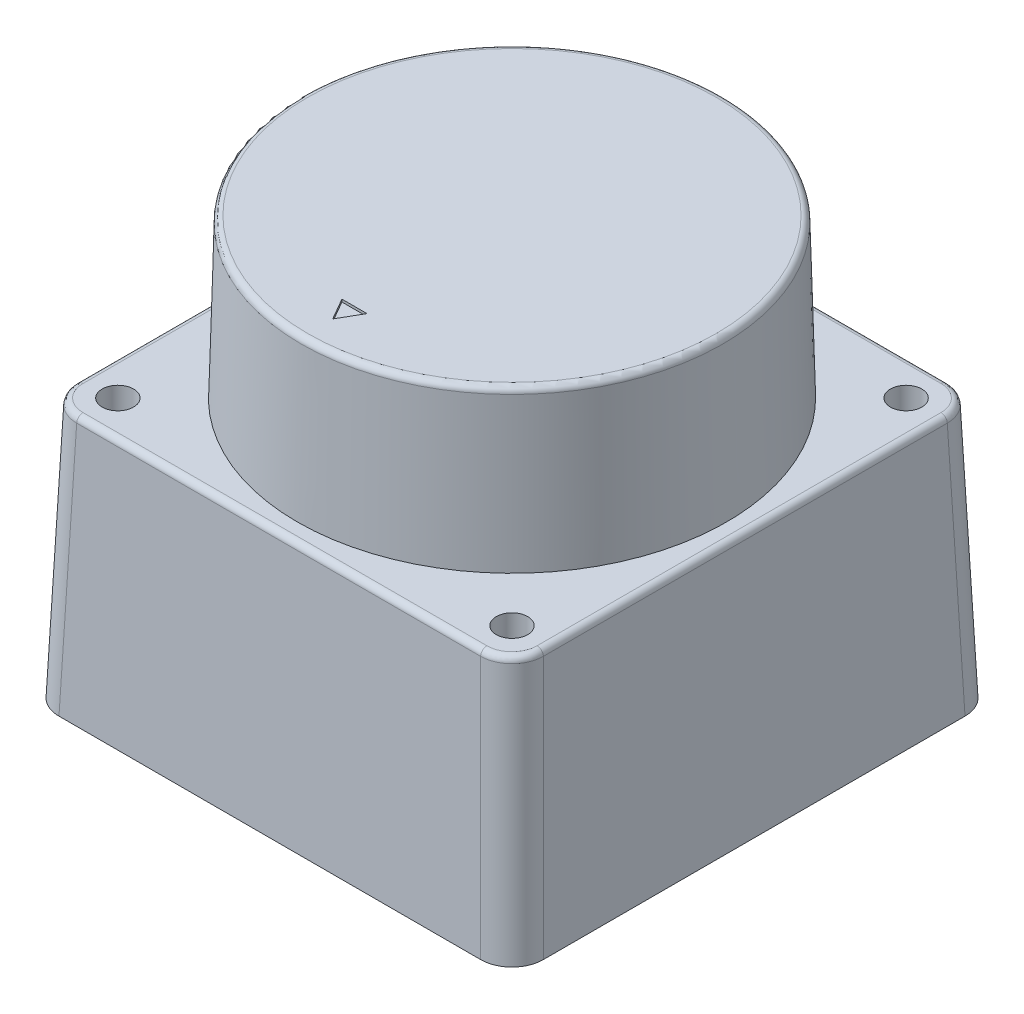
SolidWorks part; units mm, degrees
ref_plane "Płaszczyzna przednia" through (0, 0, 0) normal (0, 0, 1) x (1, 0, 0)
ref_plane "Płaszczyzna górna" through (0, 0, 0) normal (0, 1, 0) x (1, 0, 0)
ref_plane "Płaszczyzna prawa" through (0, 0, 0) normal (1, 0, 0) x (0, 0, -1)
sketch "Szkic1" plane through (0, 0, 0) normal (0, 1, 0) x (1, 0, 0)
  line L1 (-19.295, 19.295) -> (19.295, 19.295)
  line L2 (-19.295, 19.295) -> (-19.295, -19.295)
  line L3 (-19.295, -19.295) -> (19.295, -19.295)
  line L4 (19.295, 19.295) -> (19.295, -19.295)
  line L5 (-19.295, 19.295) -> (19.295, -19.295) construction
  line L6 (-19.295, -19.295) -> (19.295, 19.295) construction
  circle A0 centre (-15.7, 15.7) radius 1.25
  circle A1 centre (15.7, 15.7) radius 1.25
  circle A2 centre (15.7, -15.7) radius 1.25
  circle A3 centre (-15.7, -15.7) radius 1.25
  point P0 (0, 0)
  point P11 (0, 0)
  point P14 (0, 0)
  point P17 (0, 0)
  point P20 (0, 0)
  dimension "D3" = 2.5
  dimension "D1" = 38.59
  dimension "D2" = 38.59
  dimension "D4" = 15.7
  dimension "D5" = 15.7
  dimension "D6" = 4
extrude "Dodanie-wyciągnięcie1" add sketch "Szkic1" along normal blind 33.3
sketch "Szkic3" plane through (0, 33.3, 0) normal (0, 1, 0) x (1, 0, 0)
  circle A0 centre (0, 0) radius 17.645
  dimension "D1" = 35.29
extrude "Wytnij-wyciągnięcie1" cut sketch "Szkic3" against normal blind 12.6 flip side to cut
draft "Pochylenie2" type of draft neutral plane draft angle 2 faces to draft 4 face at (19.295, 10.35, 0) face at (0, 10.35, 19.295) face at (-19.295, 10.35, 0) face at (0, 10.35, -19.295) neutral plane through (0, 0, 0) neutral plane normal (0, -1, 0) reverse direction yes parameters "D1"=2
draft "Pochylenie3" type of draft neutral plane draft angle 1.5 faces to draft 1 face at (0, 20.7, 17.645) neutral plane through (0, 0, 0) neutral plane normal (0, -1, 0) reverse direction yes parameters "D1"=1.5
fillet "Zaokrąglenie2" radius 2.5 4 edges at (18.9336, 10.35, -18.9336) (-18.9336, 10.35, -18.9336) (-18.9336, 10.35, 18.9336) (18.9336, 10.35, 18.9336)
fillet "Zaokrąglenie3" radius 0.5 8 edges at (-17.8405, 20.7, -17.8405) (0, 20.7, -18.5721) (17.8405, 20.7, -17.8405) (18.5721, 20.7, 0) (17.8405, 20.7, 17.8405) (0, 20.7, 18.5721) (-17.8405, 20.7, 17.8405) (-18.5721, 20.7, 0)
fillet "Zaokrąglenie4" radius 0.5 1 edges at (0, 33.3, 16.773)
sketch "Szkic4" plane through (0, 33.3, 0) normal (0, 1, 0) x (1, 0, 0)
  line L1 (-1, -12.55) -> (1, -12.55)
  line L2 (1, -12.55) -> (0, -14.282)
  line L3 (0, -14.282) -> (-1, -12.55)
  point P8 (0, 0)
  point P10 (0, 0)
  dimension "D1" = 2
  dimension "D2" = 2
  dimension "D3" = 2
extrude "Wytnij-wyciągnięcie2" cut sketch "Szkic4" against normal blind 0.2
